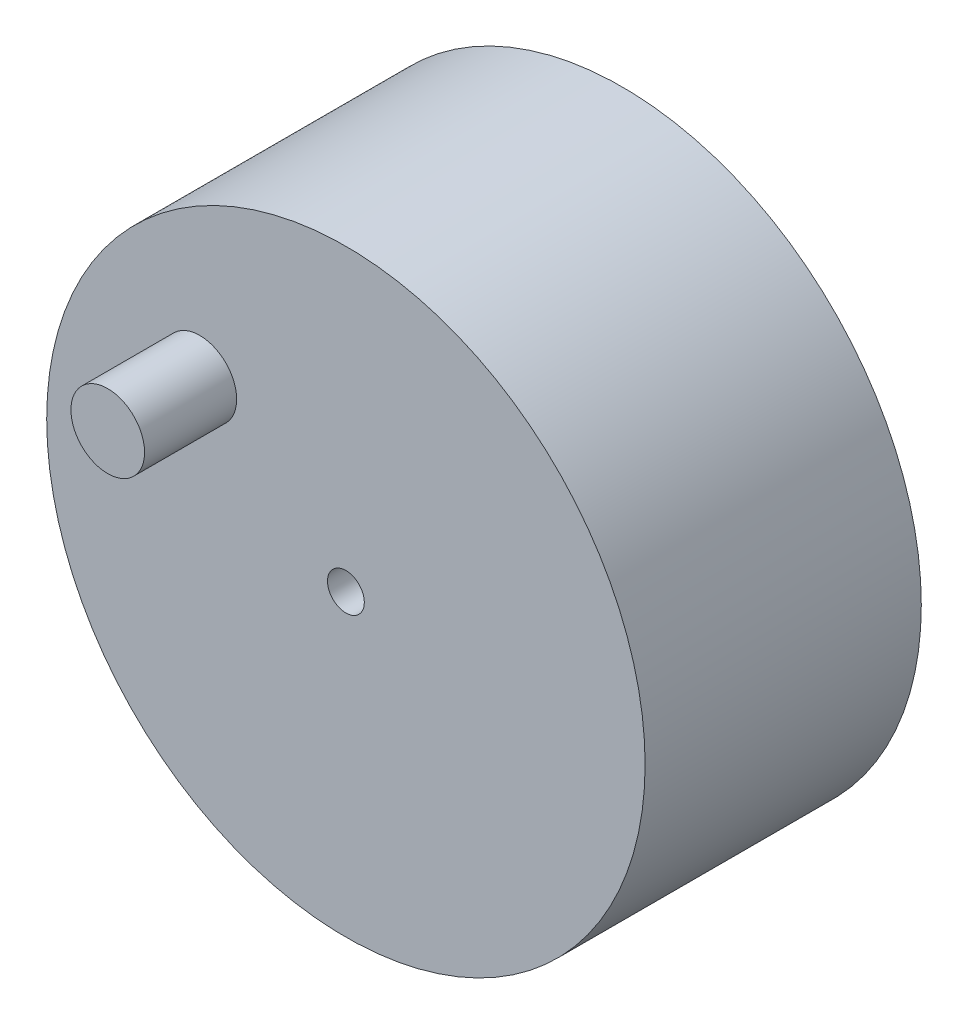
SolidWorks part; units mm, degrees
ref_plane "Plan de face" through (0, 0, 0) normal (0, 0, 1) x (1, 0, 0)
ref_plane "Plan de dessus" through (0, 0, 0) normal (0, 1, 0) x (1, 0, 0)
ref_plane "Plan de droite" through (0, 0, 0) normal (1, 0, 0) x (0, 0, -1)
sketch "Esquisse1" plane through (0, 0, 0) normal (0, 0, 1) x (1, 0, 0)
  circle A0 centre (0, 0) radius 32.5
  circle A1 centre (0, 0) radius 2
  dimension "D1" = 4
  dimension "D2" = 65
extrude "Boss.-Extru.1" add sketch "Esquisse1" along normal blind 30
sketch "Esquisse2" plane through (0, 0, 30) normal (0, 0, 1) x (1, 0, 0)
  circle A0 centre (-15.8675, 12.1747) radius 4
  circle A1 centre (0, 0) radius 32.5 construction
  dimension "D2" = 8
  dimension "D1" = 20
extrude "Boss.-Extru.2" add sketch "Esquisse2" along normal blind 10
